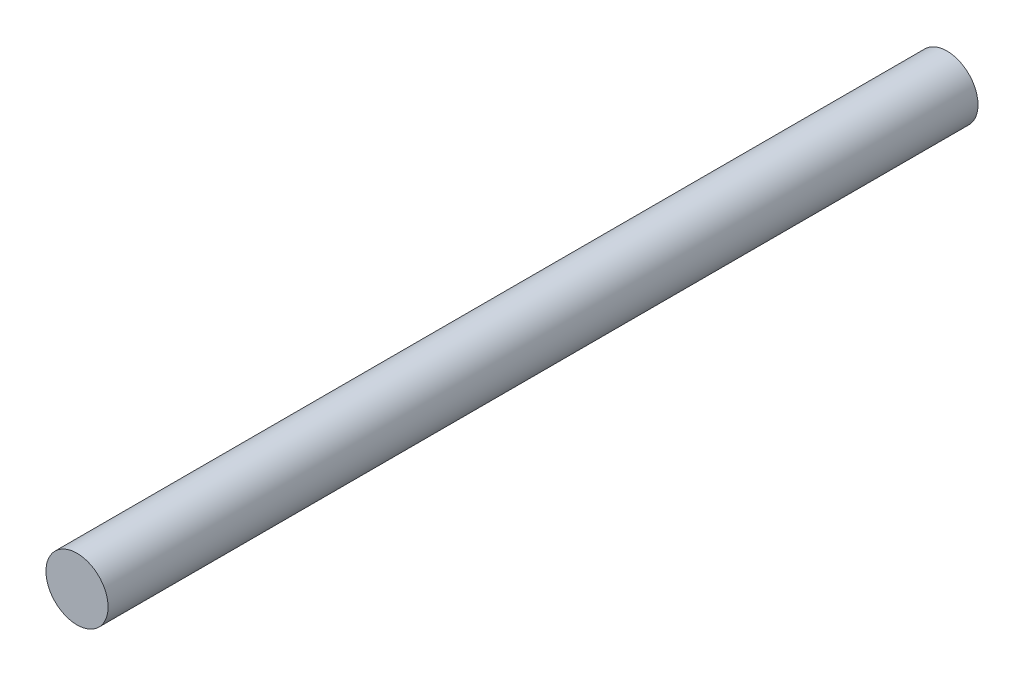
SolidWorks part; units mm, degrees
ref_plane "前视基准面" through (0, 0, 0) normal (0, 0, 1) x (1, 0, 0)
ref_plane "上视基准面" through (0, 0, 0) normal (0, 1, 0) x (1, 0, 0)
ref_plane "右视基准面" through (0, 0, 0) normal (1, 0, 0) x (0, 0, -1)
sketch "草图1" plane through (0, 0, 0) normal (0, 0, 1) x (1, 0, 0)
  circle A0 centre (0, 0) radius 2.5
  point P3 (0, 0)
  dimension "D1" = 5
extrude "凸台-拉伸1" add sketch "草图1" along normal mid plane 70
